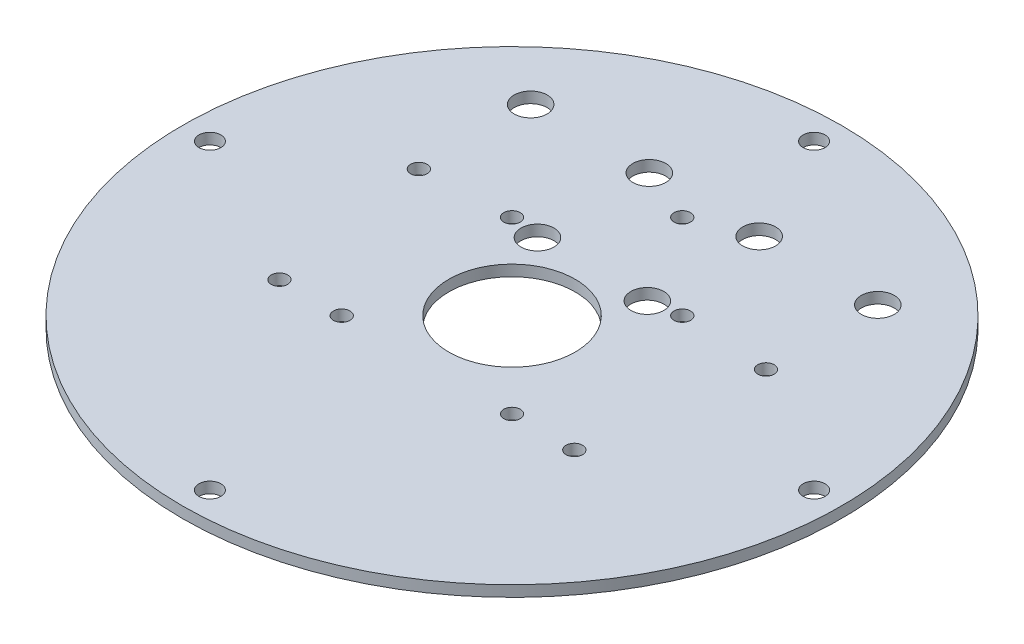
SolidWorks part; units mm, degrees
ref_plane "前视基准面" through (0, 0, 0) normal (0, 0, 1) x (1, 0, 0)
ref_plane "上视基准面" through (0, 0, 0) normal (0, 1, 0) x (1, 0, 0)
ref_plane "右视基准面" through (0, 0, 0) normal (1, 0, 0) x (0, 0, -1)
sketch "草图1" plane through (0, 0, 0) normal (0, 1, 0) x (1, 0, 0)
  circle A0 centre (0, 0) radius 60
  circle A5 centre (0, 31) radius 1.5
  circle A6 centre (26.8468, -15.5) radius 1.5
  circle A7 centre (-26.8468, -15.5) radius 1.5
  point P11 (0, 0)
  point P14 (0, 0)
  dimension "D1" = 3
extrude "凸台-拉伸1" add sketch "草图1" along normal blind 2
sketch "草图3" plane through (0, 2, 0) normal (0, 1, 0) x (1, 0, 0)
  circle A0 centre (0, 0) radius 11.5
extrude "切除-拉伸3" cut sketch "草图3" against normal blind 2
sketch "草图4" plane through (0, 2, 0) normal (0, 1, 0) x (1, 0, 0)
  circle A0 centre (-15.5, 15.5) radius 1.5
  circle A1 centre (15.5, 15.5) radius 1.5
  circle A2 centre (15.5, -15.5) radius 1.5
  circle A3 centre (-15.5, -15.5) radius 1.5
  point P0 (0, 0)
  point P16 (0, 0)
  dimension "D1" = 4
extrude "切除-拉伸4" cut sketch "草图4" against normal blind 2
sketch "草图5" plane through (0, 0, 0) normal (0, -1, 0) x (1, 0, 0)
  circle A0 centre (10, -14.64) radius 3
  circle A1 centre (-10, -14.64) radius 3
extrude "切除-拉伸5" cut sketch "草图5" against normal blind 10
sketch "草图6" plane through (0, 0, 0) normal (0, -1, 0) x (1, 0, 0)
  circle A0 centre (0, 55) radius 2
  circle A1 centre (55, 0) radius 2
  circle A2 centre (0, -55) radius 2
  circle A3 centre (-55, 0) radius 2
  point P14 (0, 0)
  dimension "D1" = 4
extrude "切除-拉伸6" cut sketch "草图6" against normal blind 10
sketch "草图7" plane through (0, 0, 0) normal (0, -1, 0) x (1, 0, 0)
  circle A0 centre (10, -35) radius 3
  circle A1 centre (-10, -35) radius 3
extrude "切除-拉伸7" cut sketch "草图7" against normal blind 10
sketch "草图8" plane through (0, 0, 0) normal (0, -1, 0) x (1, 0, 0)
  circle A0 centre (31.6, -35) radius 3
  circle A1 centre (-31.6, -35) radius 3
extrude "切除-拉伸8" cut sketch "草图8" against normal blind 10
sketch "草图9" plane through (0, 0, 0) normal (0, -1, 0) x (1, 0, 0)
  circle A0 centre (-31.6, -14.64) radius 1.5
  circle A1 centre (31.6, -14.64) radius 1.5
extrude "切除-拉伸9" cut sketch "草图9" against normal blind 10
